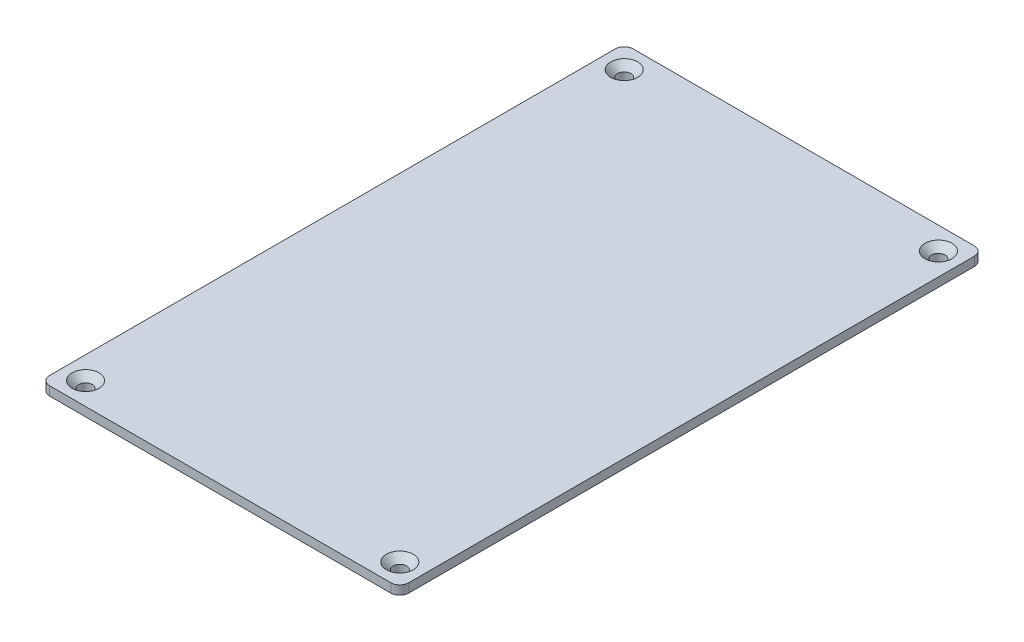
SolidWorks part; units mm, degrees
ref_plane "Front Plane" through (0, 0, 0) normal (0, 0, 1) x (1, 0, 0)
ref_plane "Top Plane" through (0, 0, 0) normal (0, 1, 0) x (1, 0, 0)
ref_plane "Right Plane" through (0, 0, 0) normal (1, 0, 0) x (0, 0, -1)
sketch "Sketch1" plane through (0, 0, 0) normal (0, 1, 0) x (1, 0, 0)
  line L1 (-37.8, 62.8) -> (37.8, 62.8)
  line L2 (-37.8, 62.8) -> (-37.8, -62.8)
  line L3 (-37.8, -62.8) -> (37.8, -62.8)
  line L4 (37.8, 62.8) -> (37.8, -62.8)
  line L5 (-37.8, 62.8) -> (37.8, -62.8) construction
  line L6 (-37.8, -62.8) -> (37.8, 62.8) construction
  point P0 (0, 0)
  dimension "D1" = 75.6
  dimension "D2" = 125.6
extrude "Boss-Extrude1" add sketch "Sketch1" along normal blind 1.8
sketch "Sketch2" plane through (0, 1.8, 0) normal (0, 1, 0) x (1, 0, 0)
  line L1 (-40, 65) -> (40, 65)
  line L2 (-40, 65) -> (-40, -65)
  line L3 (-40, -65) -> (40, -65)
  line L4 (40, 65) -> (40, -65)
  line L5 (-40, 65) -> (40, -65) construction
  line L6 (-40, -65) -> (40, 65) construction
  point P0 (0, 0)
  dimension "D1" = 80
  dimension "D2" = 130
extrude "Boss-Extrude2" add sketch "Sketch2" along normal blind 2
sketch "Sketch3" plane through (0, 3.8, 0) normal (0, 1, 0) x (1, 0, 0)
  line L0 (0, 65) -> (0, -65) construction
  line L1 (40, 65) -> (-40, 65) construction
  line L2 (-40, -65) -> (40, -65) construction
  line L3 (-40, 0) -> (40, 0) construction
  line L4 (-40, 65) -> (-40, -65) construction
  line L5 (40, -65) -> (40, 65) construction
  circle A0 centre (-35, 60) radius 1.5
  circle A1 centre (35, 60) radius 1.5
  circle A2 centre (35, -60) radius 1.5
  circle A3 centre (-35, -60) radius 1.5
  dimension "D1" = 3
  dimension "D2" = 70
  dimension "D3" = 120
extrude "Cut-Extrude1" cut sketch "Sketch3" against normal through all
chamfer "Chamfer1" distance 1.5 angle 45 4 edges at (-35, 3.8, 58.5) (35, 3.8, 61.5) (35, 3.8, -61.5) (-35, 3.8, -58.5)
fillet "Fillet1" radius 2 8 edges at (-40, 2.8, 65) (-37.8, 0.9, 62.8) (40, 2.8, 65) (37.8, 0.9, 62.8) (40, 2.8, -65) (37.8, 0.9, -62.8) (-37.8, 0.9, -62.8) (-40, 2.8, -65)
